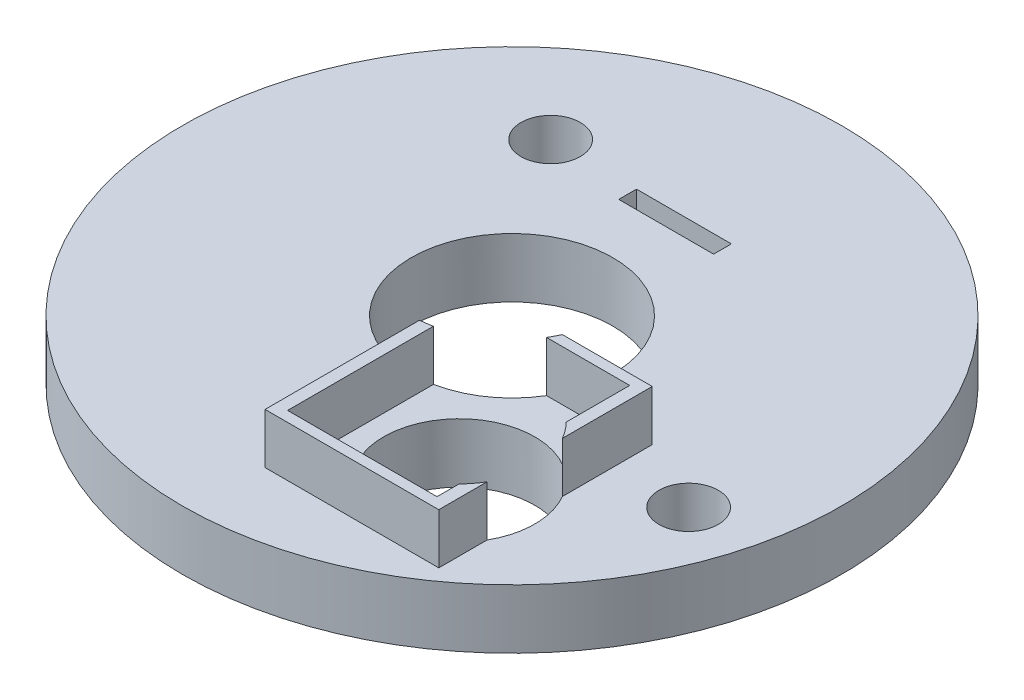
SolidWorks part; units mm, degrees
ref_plane "Front Plane" through (0, 0, 0) normal (0, 0, 1) x (1, 0, 0)
ref_plane "Top Plane" through (0, 0, 0) normal (0, 1, 0) x (1, 0, 0)
ref_plane "Right Plane" through (0, 0, 0) normal (1, 0, 0) x (0, 0, -1)
sketch "Sketch1" plane through (0, 0, 0) normal (0, 1, 0) x (1, 0, 0)
  circle A0 centre (0, 0) radius 55.585
  circle A1 centre (0, 0) radius 17
  dimension "D1" = 111.17
  dimension "D2" = 34
extrude "Boss-Extrude1" add sketch "Sketch1" against normal blind 10
sketch "Sketch2" plane through (0, 0, 0) normal (0, 1, 0) x (1, 0, 0)
  line L0 (0, 0) -> (0, -25)
  line L1 (0, -25) -> (16, -25)
  line L3 (1.35, -7) -> (30.65, -7)
  line L4 (1.35, -7) -> (1.35, -43)
  line L5 (1.35, -43) -> (30.65, -43)
  line L6 (30.65, -7) -> (30.65, -43)
  line L7 (1.35, -7) -> (30.65, -43) construction
  line L8 (1.35, -43) -> (30.65, -7) construction
  line L9 (3.4, -8.75) -> (28.6, -8.75)
  line L10 (3.4, -8.75) -> (3.4, -41.25)
  line L11 (3.4, -41.25) -> (28.6, -41.25)
  line L12 (28.6, -8.75) -> (28.6, -41.25)
  line L13 (3.4, -8.75) -> (28.6, -41.25) construction
  line L14 (3.4, -41.25) -> (28.6, -8.75) construction
  dimension "D1" = 25
  dimension "D2" = 16
  dimension "D3" = 29.3
  dimension "D4" = 36
  dimension "D5" = 25.2
  dimension "D6" = 32.5
extrude "Boss-Extrude2" add sketch "Sketch2" along normal blind 8.5 contours L4 L3 L6 L5 | L10 L9 L12 L11
sketch "Sketch4" plane through (0, 0, 0) normal (0, 1, 0) x (1, 0, 0)
  line L0 (28.6, -41.25) -> (19.6, -41.25)
  line L2 (3.4, -41.25) -> (28.6, -41.25) construction
  line L3 (19.6, -41.25) -> (19.6, -28.5)
  circle A0 centre (19.6, -28.5) radius 12.75
  dimension "D1" = 9
  dimension "D2" = 12.75
extrude "Cut-Extrude1" cut sketch "Sketch4" against normal blind 10 and the other way blind 10 contours A0
sketch "Sketch5" plane through (0, 0, 0) normal (0, 1, 0) x (1, 0, 0)
  circle A0 centre (0, 0) radius 17
extrude "Cut-Extrude2" cut sketch "Sketch5" along normal blind 10
sketch "Sketch6" plane through (0, 0, 0) normal (0, 1, 0) x (1, 0, 0)
  circle A0 centre (42.8778, -13.0882) radius 5
  dimension "D1" = 10
extrude "Cut-Extrude3" cut sketch "Sketch6" against normal blind 10
sketch "Sketch8" plane through (0, 0, 0) normal (0, 1, 0) x (1, 0, 0)
  line L0 (0, 0) -> (0, 27.5)
  line L2 (-8, 29) -> (8, 29)
  line L3 (-8, 29) -> (-8, 26)
  line L4 (-8, 26) -> (8, 26)
  line L5 (8, 29) -> (8, 26)
  line L6 (-8, 29) -> (8, 26) construction
  line L7 (-8, 26) -> (8, 29) construction
  circle A0 centre (-22.4827, 29) radius 5
  dimension "D4" = 10
  dimension "D1" = 27.5
  dimension "D2" = 16
  dimension "D3" = 3
extrude "Cut-Extrude4" cut sketch "Sketch8" against normal blind 10 contours L3 L2 L5 L4 | A0
